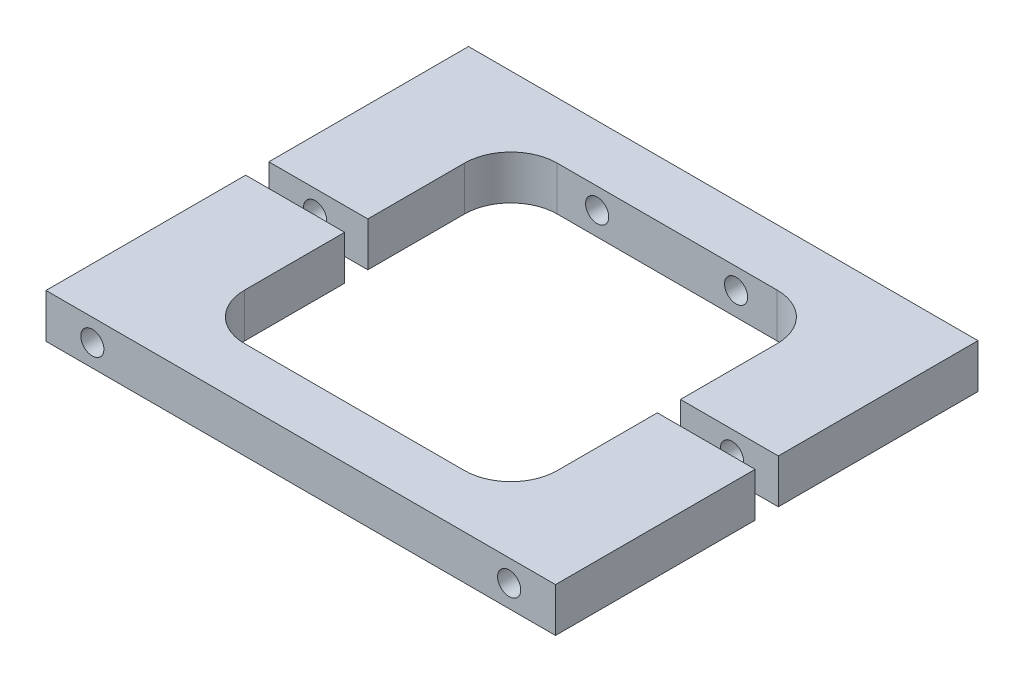
SolidWorks part; units mm, degrees
ref_plane "Plano frontal" through (0, 0, 0) normal (0, 0, 1) x (1, 0, 0)
ref_plane "Plano superior" through (0, 0, 0) normal (0, 1, 0) x (1, 0, 0)
ref_plane "Plano direito" through (0, 0, 0) normal (1, 0, 0) x (0, 0, -1)
sketch "Esboço1" plane through (0, 0, 0) normal (0, 1, 0) x (1, 0, 0)
  line L4 (55, 45) -> (-55, -45) construction
  line L5 (-55, 45) -> (55, 45)
  line L6 (-55, 45) -> (-55, -45)
  line L7 (-55, -45) -> (55, -45)
  line L8 (55, 45) -> (55, -45)
  dimension "D1" = 110
  dimension "D2" = 90
extrude "Ressalto-extrusão1" add sketch "Esboço1" along normal blind 9.52
sketch "Esboço2" plane through (0, 9.52, 0) normal (0, 1, 0) x (1, 0, 0)
  line L0 (-23.6275, 33.995) -> (23.8725, 33.995)
  line L1 (33.8725, 23.995) -> (33.8725, -23.505)
  line L2 (23.8725, -33.505) -> (-23.6275, -33.505)
  line L3 (-33.6275, -23.505) -> (-33.6275, 23.995)
  arc A0 (33.8725, 23.995) -> (23.8725, 33.995) centre (23.8725, 23.995) ccw
  arc A1 (23.8725, -33.505) -> (33.8725, -23.505) centre (23.8725, -23.505) ccw
  arc A2 (-33.6275, -23.505) -> (-23.6275, -33.505) centre (-23.6275, -23.505) ccw
  arc A3 (-23.6275, 33.995) -> (-33.6275, 23.995) centre (-23.6275, 23.995) ccw
sketch "Esboço6" plane through (0, 9.52, 0) normal (0, 1, 0) x (1, 0, 0)
  line L0 (55, 45) -> (-55, 45) construction
  line L1 (-55, 45) -> (55, 45)
  line L2 (-55, 45) -> (-55, 46.22)
  line L3 (-55, 46.22) -> (55, 46.22)
  line L4 (55, 45) -> (55, 46.22)
  dimension "D2" = 1.22
extrude "Ressalto-extrusão3" add sketch "Esboço6" against normal blind 9.52
sketch "Esboço7" plane through (0, 0, -46.22) normal (0, 0, -1) x (-1, 0, 0)
  line L0 (55, 4.76) -> (-55, 4.76) construction
  line L1 (55, 0) -> (55, 9.52) construction
  line L2 (-55, 0) -> (-55, 9.52) construction
  line L3 (0, 0) -> (0, 9.52) construction
  line L4 (-55, 0) -> (55, 0) construction
  line L5 (-55, 9.52) -> (55, 9.52) construction
  circle A0 centre (-45, 4.76) radius 2.5
  circle A1 centre (45, 4.76) radius 2.5
  circle A2 centre (-15, 5) radius 2.5
  circle A3 centre (15, 5) radius 2.5
  circle A4 centre (45, 4.76) radius 2.5
  dimension "D1" = 5
  dimension "D3" = 2
  dimension "D2" = 10
  dimension "D4" = 40
extrude "Corte-extrusão6" cut sketch "Esboço2" against normal blind 9.52
sketch "Esboço9" plane through (0, 9.52, 0) normal (0, 1, 0) x (1, 0, 0)
  line L0 (55, 46.22) -> (-55, -45) construction
  line L3 (0, 0.61) -> (55, 0.61) construction
  line L4 (-55, 46.22) -> (55, 46.22) construction
  line L5 (-55, 46.22) -> (-55, -45) construction
  line L6 (-55, -45) -> (55, -45) construction
  line L7 (55, 46.22) -> (55, -45) construction
  line L9 (-55, 3.11) -> (55, 3.11)
  line L10 (-55, 3.11) -> (-55, -1.89)
  line L11 (-55, -1.89) -> (55, -1.89)
  line L12 (55, 3.11) -> (55, -1.89)
  dimension "D1" = 2.5
  dimension "D2" = 2.5
extrude "Corte-extrusão7" cut sketch "Esboço9" against normal blind 9.52
sketch "Esboço10" plane through (0, 0, 45) normal (0, 0, 1) x (1, 0, 0)
  line L0 (-55, 4.76) -> (55, 4.76) construction
  line L1 (-55, 9.52) -> (-55, 0) construction
  line L2 (55, 9.52) -> (55, 0) construction
  line L3 (0, 0) -> (0, 9.52) construction
  line L4 (-55, 0) -> (55, 0) construction
  line L5 (-55, 9.52) -> (55, 9.52) construction
  circle A0 centre (-45, 4.76) radius 2.5
  circle A1 centre (45, 4.76) radius 2.5
  dimension "D2" = 5
  dimension "D1" = 10
extrude "Corte-extrusão8" cut sketch "Esboço10" against normal blind 70
extrude "Corte-extrusão9" cut sketch "Esboço7" against normal blind 15 contours A3 | A1 | A2 | A0
